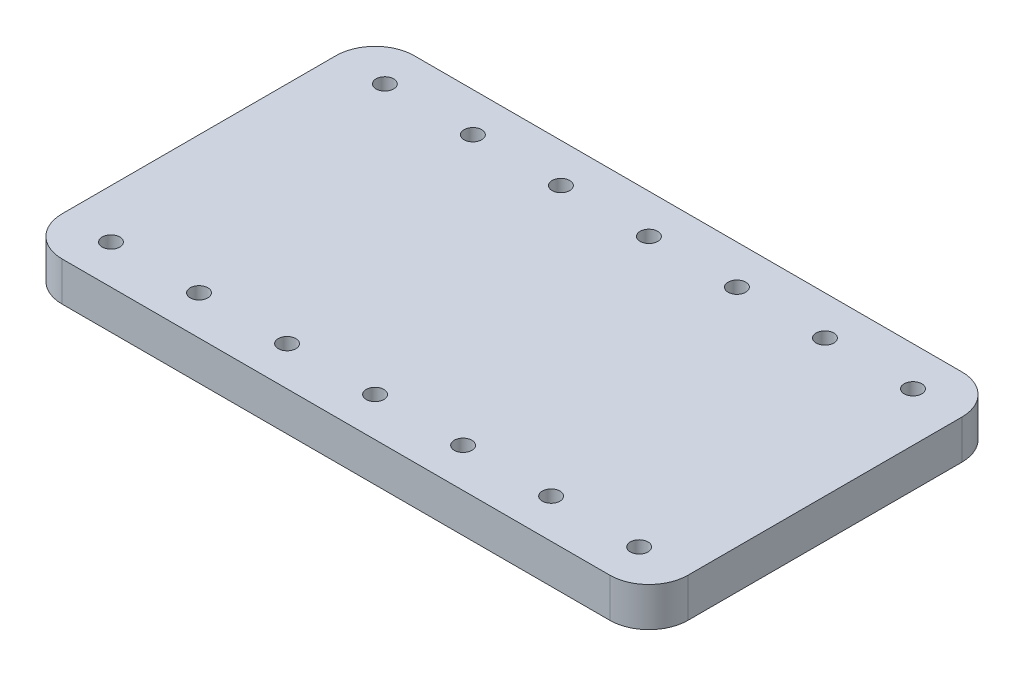
SolidWorks part; units mm, degrees
material "ABS"
ref_plane "Front Plane" through (0, 0, 0) normal (0, 0, 1) x (1, 0, 0)
ref_plane "Top Plane" through (0, 0, 0) normal (0, 1, 0) x (1, 0, 0)
ref_plane "Right Plane" through (0, 0, 0) normal (1, 0, 0) x (0, 0, -1)
sketch "Sketch1" plane through (0, 0, 0) normal (0, 1, 0) x (1, 0, 0)
  line L0 (0, 0) -> (-80, 0) construction
  line L1 (-80, 45) -> (80, 45)
  line L2 (-80, 45) -> (-80, -45)
  line L3 (-80, -45) -> (80, -45)
  line L4 (80, 45) -> (80, -45)
  line L5 (0, 0) -> (0, 45) construction
  line L6 (-67.5, 35) -> (-22.5, 35) construction
  line L7 (-22.5, 35) -> (22.5, 35) construction
  line L8 (22.5, 35) -> (67.5, 35) construction
  line L9 (67.5, 35) -> (67.5, -35) construction
  line L10 (67.5, -35) -> (22.5, -35) construction
  line L11 (22.5, -35) -> (-22.5, -35) construction
  line L12 (-22.5, -35) -> (-67.5, -35) construction
  line L13 (-67.5, -35) -> (-67.5, 35) construction
  circle A0 centre (-67.5, 35) radius 2.25
  circle A1 centre (-22.5, 35) radius 2.25
  circle A2 centre (22.5, 35) radius 2.25
  circle A3 centre (67.5, 35) radius 2.25
  circle A4 centre (67.5, -35) radius 2.25
  circle A5 centre (22.5, -35) radius 2.25
  circle A6 centre (-22.5, -35) radius 2.25
  circle A7 centre (-67.5, -35) radius 2.25
  circle A8 centre (-45, 35) radius 2.25
  circle A9 centre (45, 35) radius 2.25
  circle A10 centre (0, 35) radius 2.25
  circle A11 centre (-45, -35) radius 2.25
  circle A12 centre (0, -35) radius 2.25
  circle A13 centre (45, -35) radius 2.25
  point P24 (0, 35)
  point P28 (-67.5, 0)
  dimension "D3" = 4.5
  dimension "D5" = 45
  dimension "D1" = 90
  dimension "D2" = 160
  dimension "D4" = 70
extrude "Boss-Extrude1" add sketch "Sketch1" along normal blind 10
fillet "Fillet1" radius 10 4 edges at (-80, 5, -45) (80, 5, -45) (80, 5, 45) (-80, 5, 45)
